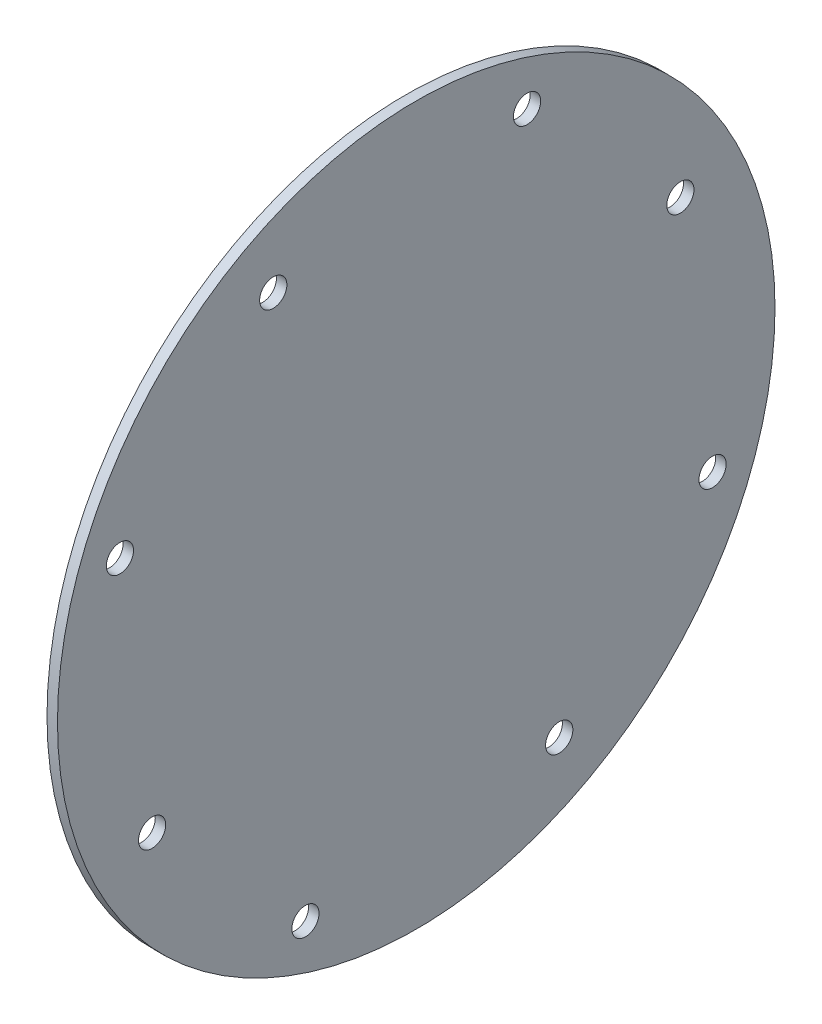
SolidWorks part; units mm, degrees
ref_plane "Front Plane" through (0, 0, 0) normal (1, 0, 0) x (0, 1, 0)
ref_plane "Top Plane" through (0, 0, 0) normal (0, 0, 1) x (0, 1, 0)
ref_plane "Right Plane" through (0, 0, 0) normal (0, 1, 0) x (-1, 0, 0)
sketch "Sketch1" plane through (0, 0, 0) normal (1, 0, 0) x (0, 1, 0)
  line L0 (0, 0) -> (26.867, 71.849)
  line L1 (26.867, 71.849) -> (64.0453, 34.6707)
  circle A0 centre (0, 0) radius 86.995
  circle A1 centre (26.867, 71.849) radius 3.302
  circle A2 centre (64.0453, 34.6707) radius 3.302
  circle A3 centre (71.849, -26.867) radius 3.302
  circle A4 centre (34.6707, -64.0453) radius 3.302
  circle A5 centre (-26.867, -71.849) radius 3.302
  circle A6 centre (-64.0453, -34.6707) radius 3.302
  circle A7 centre (-71.849, 26.867) radius 3.302
  circle A8 centre (-34.6707, 64.0453) radius 3.302
  point P22 (0, 0)
  dimension "D1" = 173.99
  dimension "D3" = 6.604
  dimension "D4" = 6.604
  dimension "D2" = 76.708
  dimension "D5" = 4
extrude "Boss-Extrude1" add sketch "Sketch1" along normal blind 2.54 contours A0 | A8 | A7 | A6 | A5 | A4 | A3 | A2 | A1
